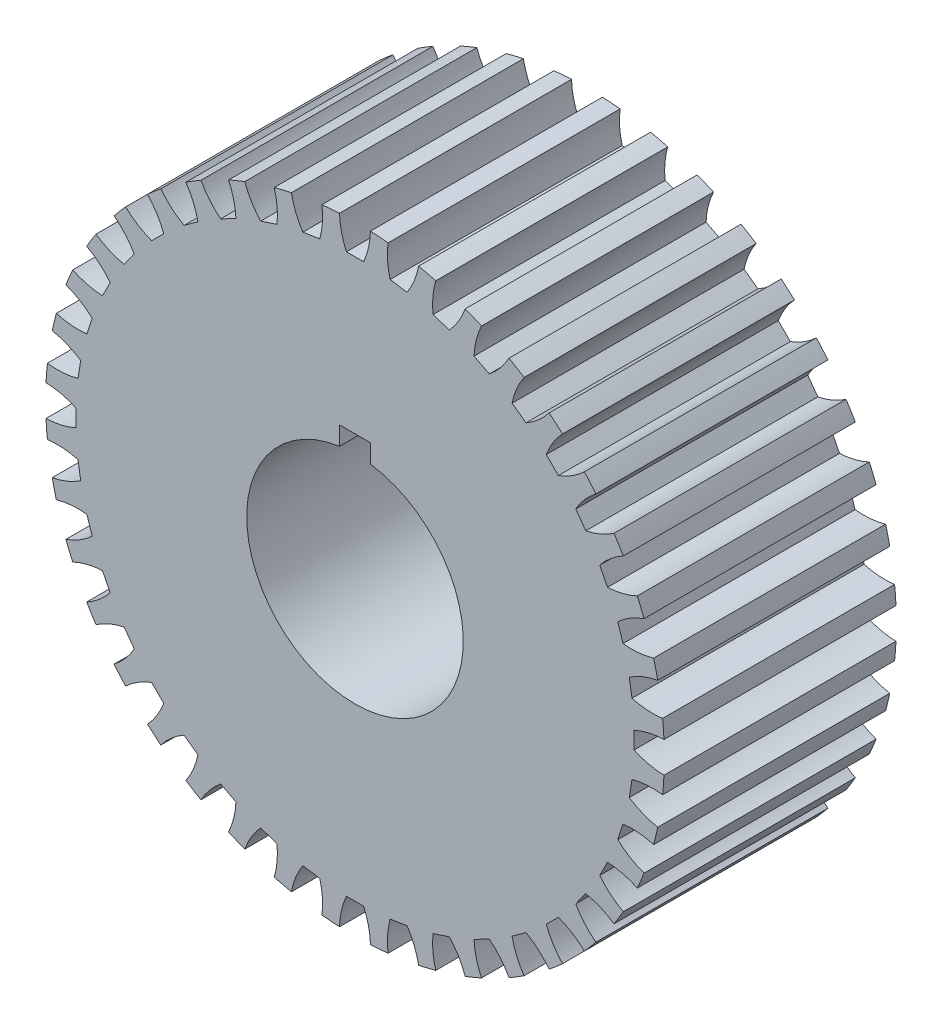
SolidWorks part; units mm, degrees
ref_plane "Front Plane" through (0, 0, 0) normal (0, 0, 1) x (1, 0, 0)
ref_plane "Top Plane" through (0, 0, 0) normal (0, 1, 0) x (1, 0, 0)
ref_plane "Right Plane" through (0, 0, 0) normal (1, 0, 0) x (0, 0, -1)
sketch "Sketch6" plane through (0, 0, 0) normal (0, 0, 1) x (1, 0, 0)
  circle A0 centre (0, 0) radius 200
extrude "Boss-Extrude4" add sketch "Sketch6" along normal blind 150 contours A0
sketch "Sketch7" plane through (0, 0, 0) normal (0, 0, 1) x (1, 0, 0)
  line L1 (10, 81.282) -> (-10, 81.282)
  line L2 (-10, 81.282) -> (-10, 69.282)
  line L3 (10, 81.282) -> (10, 69.282)
  arc A0 (-10, 69.282) -> (10, 69.282) centre (0, 0) ccw
  point P11 (0, 81.282)
  dimension "D1" = 140
  dimension "D2" = 12
  dimension "D3" = 10
extrude "Cut-Extrude6" cut sketch "Sketch7" along normal blind 150
sketch "Sketch8" plane through (0, 0, 0) normal (0, 0, 1) x (1, 0, 0)
  circle A0 centre (0, 0) radius 120
  circle A1 centre (0, 0) radius 83.5877
extrude "Cut-Extrude7" cut sketch "Sketch8" along normal blind 42.5 contours A0
ref_plane "Plane1" through (0, 0, 65) normal (0, 0, 1) x (1, 0, 0)
sketch "Sketch9" plane through (0, 0, 65) normal (0, 0, 1) x (1, 0, 0)
  line L0 (0, 0) -> (0, 200) construction
  line L1 (-5.5419, 180.41) -> (5.5419, 180.41)
  line L2 (22.7487, 179.0558) -> (33.696, 177.3219)
  line L3 (50.4791, 173.2926) -> (61.0204, 169.8676)
  line L4 (76.9666, 163.2625) -> (86.8423, 158.2305)
  line L5 (101.5589, 149.2122) -> (110.5258, 142.6973)
  line L6 (123.6504, 131.4878) -> (131.4878, 123.6504)
  line L7 (142.6973, 110.5258) -> (149.2122, 101.5589)
  line L8 (158.2305, 86.8423) -> (163.2625, 76.9666)
  line L9 (169.8676, 61.0204) -> (173.2926, 50.4791)
  line L10 (177.3219, 33.696) -> (179.0558, 22.7487)
  line L11 (180.41, 5.5419) -> (180.41, -5.5419)
  line L12 (179.0558, -22.7487) -> (177.3219, -33.696)
  line L13 (173.2926, -50.4791) -> (169.8676, -61.0204)
  line L14 (163.2625, -76.9666) -> (158.2305, -86.8423)
  line L15 (149.2122, -101.5589) -> (142.6973, -110.5258)
  line L16 (131.4878, -123.6504) -> (123.6504, -131.4878)
  line L17 (110.5258, -142.6973) -> (101.5589, -149.2122)
  line L18 (86.8423, -158.2305) -> (76.9666, -163.2625)
  line L19 (61.0204, -169.8676) -> (50.4791, -173.2926)
  line L20 (33.696, -177.3219) -> (22.7487, -179.0558)
  line L21 (5.5419, -180.41) -> (-5.5419, -180.41)
  line L22 (-22.7487, -179.0558) -> (-33.696, -177.3219)
  line L23 (-50.4791, -173.2926) -> (-61.0204, -169.8676)
  line L24 (-76.9666, -163.2625) -> (-86.8423, -158.2305)
  line L25 (-101.5589, -149.2122) -> (-110.5258, -142.6973)
  line L26 (-123.6504, -131.4878) -> (-131.4878, -123.6504)
  line L27 (-142.6973, -110.5258) -> (-149.2122, -101.5589)
  line L28 (-158.2305, -86.8423) -> (-163.2625, -76.9666)
  line L29 (-169.8676, -61.0204) -> (-173.2926, -50.4791)
  line L30 (-177.3219, -33.696) -> (-179.0558, -22.7487)
  line L31 (-180.41, -5.5419) -> (-180.41, 5.5419)
  line L32 (-179.0558, 22.7487) -> (-177.3219, 33.696)
  line L33 (-173.2926, 50.4791) -> (-169.8676, 61.0204)
  line L34 (-163.2625, 76.9666) -> (-158.2305, 86.8423)
  line L35 (-149.2122, 101.5589) -> (-142.6973, 110.5258)
  line L36 (-131.4878, 123.6504) -> (-123.6504, 131.4878)
  line L37 (-110.5258, 142.6973) -> (-101.5589, 149.2122)
  line L38 (-86.8423, 158.2305) -> (-76.9666, 163.2625)
  line L39 (-61.0204, 169.8676) -> (-50.4791, 173.2926)
  line L40 (-33.696, 177.3219) -> (-22.7487, 179.0558)
  line L41 (0, 0) -> (0, 180.41) construction
  circle A0 centre (0, 0) radius 200 construction
  circle A1 centre (0, 0) radius 200 construction
  arc A2 (9.9969, 199.75) -> (5.5419, 180.41) centre (-39.5938, 200.9902) cw
  arc A3 (-9.9969, 199.75) -> (-5.5419, 180.41) centre (39.5938, 200.9902) ccw
  arc A4 (-9.9969, 199.75) -> (9.9969, 199.75) centre (0, 200) cw
  arc A5 (21.374, 198.8546) -> (41.1216, 195.7269) centre (31.2869, 197.5377) cw
  arc A6 (41.1216, 195.7269) -> (33.696, 177.3219) centre (-7.6646, 204.7095) cw
  arc A7 (21.374, 198.8546) -> (22.7487, 179.0558) centre (70.5481, 192.3218) ccw
  arc A8 (52.2186, 193.0627) -> (71.2337, 186.8843) centre (61.8034, 190.2113) cw
  arc A9 (71.2337, 186.8843) -> (61.0204, 169.8676) centre (24.4534, 203.3882) cw
  arc A10 (52.2186, 193.0627) -> (50.4791, 173.2926) centre (99.7653, 178.9178) ccw
  arc A11 (81.7773, 182.517) -> (99.5919, 173.4401) centre (90.7981, 178.2013) cw
  arc A12 (99.5919, 173.4401) -> (86.8423, 158.2305) centre (55.9693, 197.0588) cw
  arc A13 (81.7773, 182.517) -> (76.9666, 163.2625) centre (126.526, 161.1083) ccw
  arc A14 (109.3225, 167.4772) -> (125.4977, 155.7251) centre (117.5571, 161.8034) cw
  arc A15 (125.4977, 155.7251) -> (110.5258, 142.6973) centre (86.107, 185.8771) cw
  arc A16 (109.3225, 167.4772) -> (101.5589, 149.2122) centre (150.1711, 139.3318) ccw
  arc A17 (134.1757, 148.3134) -> (148.3134, 134.1757) centre (141.4214, 141.4214) cw
  arc A18 (148.3134, 134.1757) -> (131.4878, 123.6504) centre (114.1244, 170.1186) cw
  arc A19 (134.1757, 148.3134) -> (123.6504, 131.4878) centre (170.1186, 114.1244) ccw
  arc A20 (155.7251, 125.4977) -> (167.4772, 109.3225) centre (161.8034, 117.5571) cw
  arc A21 (167.4772, 109.3225) -> (149.2122, 101.5589) centre (139.3318, 150.1711) cw
  arc A22 (155.7251, 125.4977) -> (142.6973, 110.5258) centre (185.8771, 86.107) ccw
  arc A23 (173.4401, 99.5919) -> (182.517, 81.7773) centre (178.2013, 90.7981) cw
  arc A24 (182.517, 81.7773) -> (163.2625, 76.9666) centre (161.1083, 126.526) cw
  arc A25 (173.4401, 99.5919) -> (158.2305, 86.8423) centre (197.0588, 55.9693) ccw
  arc A26 (186.8843, 71.2337) -> (193.0627, 52.2186) centre (190.2113, 61.8034) cw
  arc A27 (193.0627, 52.2186) -> (173.2926, 50.4791) centre (178.9178, 99.7653) cw
  arc A28 (186.8843, 71.2337) -> (169.8676, 61.0204) centre (203.3882, 24.4534) ccw
  arc A29 (195.7269, 41.1216) -> (198.8546, 21.374) centre (197.5377, 31.2869) cw
  arc A30 (198.8546, 21.374) -> (179.0558, 22.7487) centre (192.3218, 70.5481) cw
  arc A31 (195.7269, 41.1216) -> (177.3219, 33.696) centre (204.7095, -7.6646) ccw
  arc A32 (199.75, 9.9969) -> (199.75, -9.9969) centre (200, 0) cw
  arc A33 (199.75, -9.9969) -> (180.41, -5.5419) centre (200.9902, 39.5938) cw
  arc A34 (199.75, 9.9969) -> (180.41, 5.5419) centre (200.9902, -39.5938) ccw
  arc A35 (198.8546, -21.374) -> (195.7269, -41.1216) centre (197.5377, -31.2869) cw
  arc A36 (195.7269, -41.1216) -> (177.3219, -33.696) centre (204.7095, 7.6646) cw
  arc A37 (198.8546, -21.374) -> (179.0558, -22.7487) centre (192.3218, -70.5481) ccw
  arc A38 (193.0627, -52.2186) -> (186.8843, -71.2337) centre (190.2113, -61.8034) cw
  arc A39 (186.8843, -71.2337) -> (169.8676, -61.0204) centre (203.3882, -24.4534) cw
  arc A40 (193.0627, -52.2186) -> (173.2926, -50.4791) centre (178.9178, -99.7653) ccw
  arc A41 (182.517, -81.7773) -> (173.4401, -99.5919) centre (178.2013, -90.7981) cw
  arc A42 (173.4401, -99.5919) -> (158.2305, -86.8423) centre (197.0588, -55.9693) cw
  arc A43 (182.517, -81.7773) -> (163.2625, -76.9666) centre (161.1083, -126.526) ccw
  arc A44 (167.4772, -109.3225) -> (155.7251, -125.4977) centre (161.8034, -117.5571) cw
  arc A45 (155.7251, -125.4977) -> (142.6973, -110.5258) centre (185.8771, -86.107) cw
  arc A46 (167.4772, -109.3225) -> (149.2122, -101.5589) centre (139.3318, -150.1711) ccw
  arc A47 (148.3134, -134.1757) -> (134.1757, -148.3134) centre (141.4214, -141.4214) cw
  arc A48 (134.1757, -148.3134) -> (123.6504, -131.4878) centre (170.1186, -114.1244) cw
  arc A49 (148.3134, -134.1757) -> (131.4878, -123.6504) centre (114.1244, -170.1186) ccw
  arc A50 (125.4977, -155.7251) -> (109.3225, -167.4772) centre (117.5571, -161.8034) cw
  arc A51 (109.3225, -167.4772) -> (101.5589, -149.2122) centre (150.1711, -139.3318) cw
  arc A52 (125.4977, -155.7251) -> (110.5258, -142.6973) centre (86.107, -185.8771) ccw
  arc A53 (99.5919, -173.4401) -> (81.7773, -182.517) centre (90.7981, -178.2013) cw
  arc A54 (81.7773, -182.517) -> (76.9666, -163.2625) centre (126.526, -161.1083) cw
  arc A55 (99.5919, -173.4401) -> (86.8423, -158.2305) centre (55.9693, -197.0588) ccw
  arc A56 (71.2337, -186.8843) -> (52.2186, -193.0627) centre (61.8034, -190.2113) cw
  arc A57 (52.2186, -193.0627) -> (50.4791, -173.2926) centre (99.7653, -178.9178) cw
  arc A58 (71.2337, -186.8843) -> (61.0204, -169.8676) centre (24.4534, -203.3882) ccw
  arc A59 (41.1216, -195.7269) -> (21.374, -198.8546) centre (31.2869, -197.5377) cw
  arc A60 (21.374, -198.8546) -> (22.7487, -179.0558) centre (70.5481, -192.3218) cw
  arc A61 (41.1216, -195.7269) -> (33.696, -177.3219) centre (-7.6646, -204.7095) ccw
  arc A62 (9.9969, -199.75) -> (-9.9969, -199.75) centre (0, -200) cw
  arc A63 (-9.9969, -199.75) -> (-5.5419, -180.41) centre (39.5938, -200.9902) cw
  arc A64 (9.9969, -199.75) -> (5.5419, -180.41) centre (-39.5938, -200.9902) ccw
  arc A65 (-21.374, -198.8546) -> (-41.1216, -195.7269) centre (-31.2869, -197.5377) cw
  arc A66 (-41.1216, -195.7269) -> (-33.696, -177.3219) centre (7.6646, -204.7095) cw
  arc A67 (-21.374, -198.8546) -> (-22.7487, -179.0558) centre (-70.5481, -192.3218) ccw
  arc A68 (-52.2186, -193.0627) -> (-71.2337, -186.8843) centre (-61.8034, -190.2113) cw
  arc A69 (-71.2337, -186.8843) -> (-61.0204, -169.8676) centre (-24.4534, -203.3882) cw
  arc A70 (-52.2186, -193.0627) -> (-50.4791, -173.2926) centre (-99.7653, -178.9178) ccw
  arc A71 (-81.7773, -182.517) -> (-99.5919, -173.4401) centre (-90.7981, -178.2013) cw
  arc A72 (-99.5919, -173.4401) -> (-86.8423, -158.2305) centre (-55.9693, -197.0588) cw
  arc A73 (-81.7773, -182.517) -> (-76.9666, -163.2625) centre (-126.526, -161.1083) ccw
  arc A74 (-109.3225, -167.4772) -> (-125.4977, -155.7251) centre (-117.5571, -161.8034) cw
  arc A75 (-125.4977, -155.7251) -> (-110.5258, -142.6973) centre (-86.107, -185.8771) cw
  arc A76 (-109.3225, -167.4772) -> (-101.5589, -149.2122) centre (-150.1711, -139.3318) ccw
  arc A77 (-134.1757, -148.3134) -> (-148.3134, -134.1757) centre (-141.4214, -141.4214) cw
  arc A78 (-148.3134, -134.1757) -> (-131.4878, -123.6504) centre (-114.1244, -170.1186) cw
  arc A79 (-134.1757, -148.3134) -> (-123.6504, -131.4878) centre (-170.1186, -114.1244) ccw
  arc A80 (-155.7251, -125.4977) -> (-167.4772, -109.3225) centre (-161.8034, -117.5571) cw
  arc A81 (-167.4772, -109.3225) -> (-149.2122, -101.5589) centre (-139.3318, -150.1711) cw
  arc A82 (-155.7251, -125.4977) -> (-142.6973, -110.5258) centre (-185.8771, -86.107) ccw
  arc A83 (-173.4401, -99.5919) -> (-182.517, -81.7773) centre (-178.2013, -90.7981) cw
  arc A84 (-182.517, -81.7773) -> (-163.2625, -76.9666) centre (-161.1083, -126.526) cw
  arc A85 (-173.4401, -99.5919) -> (-158.2305, -86.8423) centre (-197.0588, -55.9693) ccw
  arc A86 (-186.8843, -71.2337) -> (-193.0627, -52.2186) centre (-190.2113, -61.8034) cw
  arc A87 (-193.0627, -52.2186) -> (-173.2926, -50.4791) centre (-178.9178, -99.7653) cw
  arc A88 (-186.8843, -71.2337) -> (-169.8676, -61.0204) centre (-203.3882, -24.4534) ccw
  arc A89 (-195.7269, -41.1216) -> (-198.8546, -21.374) centre (-197.5377, -31.2869) cw
  arc A90 (-198.8546, -21.374) -> (-179.0558, -22.7487) centre (-192.3218, -70.5481) cw
  arc A91 (-195.7269, -41.1216) -> (-177.3219, -33.696) centre (-204.7095, 7.6646) ccw
  arc A92 (-199.75, -9.9969) -> (-199.75, 9.9969) centre (-200, 0) cw
  arc A93 (-199.75, 9.9969) -> (-180.41, 5.5419) centre (-200.9902, -39.5938) cw
  arc A94 (-199.75, -9.9969) -> (-180.41, -5.5419) centre (-200.9902, 39.5938) ccw
  arc A95 (-198.8546, 21.374) -> (-195.7269, 41.1216) centre (-197.5377, 31.2869) cw
  arc A96 (-195.7269, 41.1216) -> (-177.3219, 33.696) centre (-204.7095, -7.6646) cw
  arc A97 (-198.8546, 21.374) -> (-179.0558, 22.7487) centre (-192.3218, 70.5481) ccw
  arc A98 (-193.0627, 52.2186) -> (-186.8843, 71.2337) centre (-190.2113, 61.8034) cw
  arc A99 (-186.8843, 71.2337) -> (-169.8676, 61.0204) centre (-203.3882, 24.4534) cw
  arc A100 (-193.0627, 52.2186) -> (-173.2926, 50.4791) centre (-178.9178, 99.7653) ccw
  arc A101 (-182.517, 81.7773) -> (-173.4401, 99.5919) centre (-178.2013, 90.7981) cw
  arc A102 (-173.4401, 99.5919) -> (-158.2305, 86.8423) centre (-197.0588, 55.9693) cw
  arc A103 (-182.517, 81.7773) -> (-163.2625, 76.9666) centre (-161.1083, 126.526) ccw
  arc A104 (-167.4772, 109.3225) -> (-155.7251, 125.4977) centre (-161.8034, 117.5571) cw
  arc A105 (-155.7251, 125.4977) -> (-142.6973, 110.5258) centre (-185.8771, 86.107) cw
  arc A106 (-167.4772, 109.3225) -> (-149.2122, 101.5589) centre (-139.3318, 150.1711) ccw
  arc A107 (-148.3134, 134.1757) -> (-134.1757, 148.3134) centre (-141.4214, 141.4214) cw
  arc A108 (-134.1757, 148.3134) -> (-123.6504, 131.4878) centre (-170.1186, 114.1244) cw
  arc A109 (-148.3134, 134.1757) -> (-131.4878, 123.6504) centre (-114.1244, 170.1186) ccw
  arc A110 (-125.4977, 155.7251) -> (-109.3225, 167.4772) centre (-117.5571, 161.8034) cw
  arc A111 (-109.3225, 167.4772) -> (-101.5589, 149.2122) centre (-150.1711, 139.3318) cw
  arc A112 (-125.4977, 155.7251) -> (-110.5258, 142.6973) centre (-86.107, 185.8771) ccw
  arc A113 (-99.5919, 173.4401) -> (-81.7773, 182.517) centre (-90.7981, 178.2013) cw
  arc A114 (-81.7773, 182.517) -> (-76.9666, 163.2625) centre (-126.526, 161.1083) cw
  arc A115 (-99.5919, 173.4401) -> (-86.8423, 158.2305) centre (-55.9693, 197.0588) ccw
  arc A116 (-71.2337, 186.8843) -> (-52.2186, 193.0627) centre (-61.8034, 190.2113) cw
  arc A117 (-52.2186, 193.0627) -> (-50.4791, 173.2926) centre (-99.7653, 178.9178) cw
  arc A118 (-71.2337, 186.8843) -> (-61.0204, 169.8676) centre (-24.4534, 203.3882) ccw
  arc A119 (-41.1216, 195.7269) -> (-21.374, 198.8546) centre (-31.2869, 197.5377) cw
  arc A120 (-21.374, 198.8546) -> (-22.7487, 179.0558) centre (-70.5481, 192.3218) cw
  arc A121 (-41.1216, 195.7269) -> (-33.696, 177.3219) centre (7.6646, 204.7095) ccw
  point P13 (0, 180.41)
  point P23 (28.2223, 178.1889)
  point P31 (55.7498, 171.5801)
  point P39 (81.9044, 160.7465)
  point P47 (106.0423, 145.9548)
  point P55 (127.5691, 127.5691)
  point P63 (145.9548, 106.0423)
  point P71 (160.7465, 81.9044)
  point P79 (171.5801, 55.7498)
  point P87 (178.1889, 28.2223)
  point P95 (180.41, 0)
  point P103 (178.1889, -28.2223)
  point P111 (171.5801, -55.7498)
  point P119 (160.7465, -81.9044)
  point P127 (145.9548, -106.0423)
  point P135 (127.5691, -127.5691)
  point P143 (106.0423, -145.9548)
  point P151 (81.9044, -160.7465)
  point P159 (55.7498, -171.5801)
  point P167 (28.2223, -178.1889)
  point P175 (0, -180.41)
  point P183 (-28.2223, -178.1889)
  point P191 (-55.7498, -171.5801)
  point P199 (-81.9044, -160.7465)
  point P207 (-106.0423, -145.9548)
  point P215 (-127.5691, -127.5691)
  point P223 (-145.9548, -106.0423)
  point P231 (-160.7465, -81.9044)
  point P239 (-171.5801, -55.7498)
  point P247 (-178.1889, -28.2223)
  point P255 (-180.41, 0)
  point P263 (-178.1889, 28.2223)
  point P271 (-171.5801, 55.7498)
  point P279 (-160.7465, 81.9044)
  point P287 (-145.9548, 106.0423)
  point P295 (-127.5691, 127.5691)
  point P303 (-106.0423, 145.9548)
  point P311 (-81.9044, 160.7465)
  point P319 (-55.7498, 171.5801)
  point P327 (-28.2223, 178.1889)
  dimension "D2" = 40
  dimension "D1" = 19.59
  dimension "D3" = 180.41
  dimension "D4" = 17.26
  dimension "D6" = 11.0838
extrude "Cut-Extrude11" cut sketch "Sketch9" along normal through all both and the other way through all
